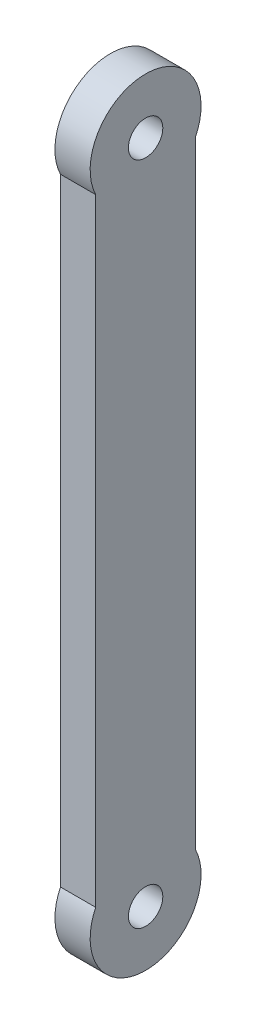
SolidWorks part; units mm, degrees
ref_plane "Front Plane" through (0, 0, 0) normal (0, 0, 1) x (1, 0, 0)
ref_plane "Top Plane" through (0, 0, 0) normal (0, 1, 0) x (1, 0, 0)
ref_plane "Right Plane" through (0, 0, 0) normal (1, 0, 0) x (0, 0, -1)
sketch "Sketch1" plane through (0, 0, 0) normal (1, 0, 0) x (0, 0, -1)
  line L0 (0, 0) -> (-4.5, -2.1794) construction
  line L2 (4.5, -2.1794) -> (4.5, -57.8206)
  line L3 (4.5, -57.8206) -> (-4.5, -57.8206) construction
  line L4 (-4.5, -2.1794) -> (-4.5, -57.8206)
  line L5 (4.5, -2.1794) -> (-4.5, -2.1794) construction
  line L6 (0, 0) -> (4.5, -2.1794) construction
  circle A0 centre (0, 0) radius 1.55
  arc A1 (4.5, -2.1794) -> (-4.5, -2.1794) centre (0, 0) ccw
  arc A2 (-4.5, -57.8206) -> (4.5, -57.8206) centre (0, -60) ccw
  circle A3 centre (0, -60) radius 1.55
  dimension "D1" = 3.1
  dimension "D2" = 10
  dimension "D4" = 10
  dimension "D6" = 3.1
  dimension "D3" = 9
  dimension "D5" = 60
extrude "Boss-Extrude3" add sketch "Sketch1" along normal blind 3.175
